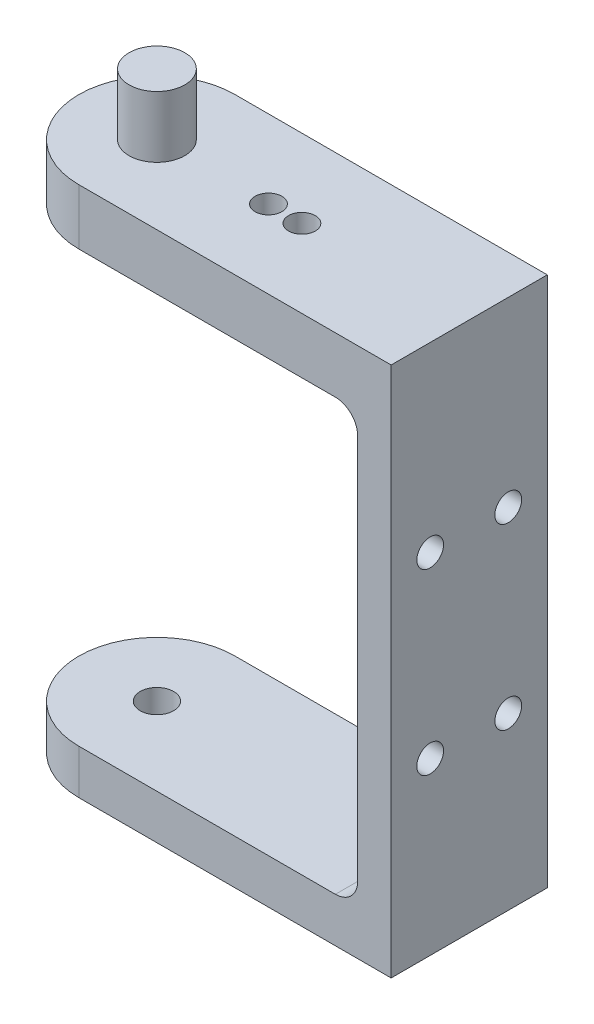
SolidWorks part; units mm, degrees
material "ABS"
ref_plane "Front Plane" through (0, 0, 0) normal (0, 0, 1) x (1, 0, 0)
ref_plane "Top Plane" through (0, 0, 0) normal (0, 1, 0) x (1, 0, 0)
ref_plane "Right Plane" through (0, 0, 0) normal (1, 0, 0) x (0, 0, -1)
ref_plane "Y+19_30" through (0, 19.3, 0) normal (0, 1, 0) x (1, 0, 0)
sketch "Sketch1" plane through (0, 19.3, 0) normal (0, 1, 0) x (1, 0, 0)
  line L0 (5.5, -7) -> (33.5, -7)
  line L1 (33.5, -7) -> (33.5, 7)
  line L2 (33.5, 7) -> (5.5, 7)
  arc A0 (5.5, 7) -> (5.5, -7) centre (5.5, 0) ccw
extrude "Boss-Extrude1" add sketch "Sketch1" along normal blind 5
ref_plane "Y-23_30" through (0, -23.3, 0) normal (0, 1, 0) x (1, 0, 0)
sketch "Sketch2" plane through (0, -23.3, 0) normal (0, 1, 0) x (1, 0, 0)
  line L0 (5.5, -7) -> (33.5, -7)
  line L1 (33.5, -7) -> (33.5, 7)
  line L2 (33.5, 7) -> (5.5, 7)
  arc A0 (5.5, 7) -> (5.5, -7) centre (5.5, 0) ccw
extrude "Boss-Extrude2" add sketch "Sketch2" along normal blind 4
sketch "Sketch3" plane through (0, 0, 0) normal (0, 0, 1) x (1, 0, 0)
  line L0 (7.7, -23.3) -> (-7.7, -23.3) construction
  line L1 (30.5, -23.3) -> (33.5, -23.3)
  line L2 (30.5, -23.3) -> (30.5, 24.3)
  line L3 (30.5, 24.3) -> (33.5, 24.3)
  line L4 (33.5, -23.3) -> (33.5, 24.3)
extrude "Boss-Extrude3" add sketch "Sketch3" along normal mid plane 14
ref_plane "Y+24_30" through (0, 24.3, 0) normal (0, 1, 0) x (1, 0, 0)
sketch "Sketch4" plane through (0, 24.3, 0) normal (0, 1, 0) x (1, 0, 0)
  circle A0 centre (5.5, 0) radius 2.5
extrude "Boss-Extrude4" add sketch "Sketch4" along normal blind 5.5
sketch "Sketch5" plane through (0, 19.3, 0) normal (0, 1, 0) x (1, 0, 0)
  circle A0 centre (5.5, 0) radius 3.7
extrude "Cut-Extrude2" cut sketch "Sketch5" along normal blind 1.6
sketch "Sketch6" plane through (0, 19.3, 0) normal (0, 1, 0) x (1, 0, 0)
  line L0 (5.5, -2.7) -> (20.7, -2.7)
  line L1 (20.7, -2.7) -> (20.7, 2.7)
  line L2 (20.7, 2.7) -> (5.5, 2.7)
  arc A0 (5.5, 2.7) -> (5.5, -2.7) centre (5.5, 0) ccw
extrude "Cut-Extrude4" cut sketch "Sketch6" along normal blind 1.6
ref_plane "Y+20_90" through (0, 20.9, 0) normal (0, 1, 0) x (1, 0, 0)
sketch "Sketch7" plane through (0, 20.9, 0) normal (0, 1, 0) x (1, 0, 0)
  circle A0 centre (5.5, 0) radius 2.5
extrude "Cut-Extrude6" cut sketch "Sketch7" along normal blind 1.6
sketch "Sketch8" plane through (0, -23.3, 0) normal (0, 1, 0) x (1, 0, 0)
  circle A0 centre (5.5, 0) radius 1.5
extrude "Cut-Extrude8" cut sketch "Sketch8" along normal blind 4
hole_wizard "M2 Clearance Hole1" positions "Sketch10" profile "Sketch9" hole size "M2" standard "ISO"
sketch "Sketch10" plane through (0, 24.3, 0) normal (0, 1, 0) x (1, 0, 0)
  point P0 (15.5, 0)
sketch "Sketch9" plane through (15.5, 24.3, 0) normal (1, 0, 0) x (0, 0, 1)
  line L0 (0, 0) -> (0, 5.721)
  line L1 (0, 5.721) -> (1.2, 5)
  line L2 (1.2, 5) -> (1.2, 0)
  line L5 (1.2, 0) -> (0, 0)
  line L10 (0, 5.721) -> (-1.2, 5) construction
  line L11 (0, -6.35) -> (0, 107.95) construction
  dimension "Hole Dia." = 2.4
  dimension "Hole Depth" = 5
  dimension "Drill Angle" = 118
hole_wizard "M2 Clearance Hole2" positions "Sketch12" profile "Sketch11" hole size "M2" standard "ISO"
sketch "Sketch12" plane through (0, 24.3, 0) normal (0, 1, 0) x (1, 0, 0)
  point P0 (18.5, 0)
sketch "Sketch11" plane through (18.5, 24.3, 0) normal (1, 0, 0) x (0, 0, 1)
  line L0 (0, 0) -> (0, 5.721)
  line L1 (0, 5.721) -> (1.2, 5)
  line L2 (1.2, 5) -> (1.2, 0)
  line L5 (1.2, 0) -> (0, 0)
  line L10 (0, 5.721) -> (-1.2, 5) construction
  line L11 (0, -6.35) -> (0, 107.95) construction
  dimension "Hole Dia." = 2.4
  dimension "Hole Depth" = 5
  dimension "Drill Angle" = 118
hole_wizard "M2 Clearance Hole3" positions "Sketch14" profile "Sketch13" hole size "M2" standard "ISO"
sketch "Sketch14" plane through (33.5, 0, 0) normal (1, 0, 0) x (0, 0, -1)
  point P0 (3.5, -8)
sketch "Sketch13" plane through (33.5, -8, -3.5) normal (0, 1, 0) x (0, 0, -1)
  line L0 (0, 0) -> (0, 35)
  line L1 (0, 35) -> (1.2, 35)
  line L2 (1.2, 35) -> (1.2, 0)
  line L5 (1.2, 0) -> (0, 0)
  line L11 (0, -6.35) -> (0, 107.95) construction
  dimension "Thru Hole Dia." = 2.4
  dimension "Thru Hole Depth" = 35
hole_wizard "M2 Clearance Hole4" positions "Sketch16" profile "Sketch15" hole size "M2" standard "ISO"
sketch "Sketch16" plane through (33.5, 0, 0) normal (1, 0, 0) x (0, 0, -1)
  point P0 (-3.5, -8)
sketch "Sketch15" plane through (33.5, -8, 3.5) normal (0, 1, 0) x (0, 0, -1)
  line L0 (0, 0) -> (0, 35)
  line L1 (0, 35) -> (1.2, 35)
  line L2 (1.2, 35) -> (1.2, 0)
  line L5 (1.2, 0) -> (0, 0)
  line L11 (0, -6.35) -> (0, 107.95) construction
  dimension "Thru Hole Dia." = 2.4
  dimension "Thru Hole Depth" = 35
hole_wizard "M2 Clearance Hole5" positions "Sketch18" profile "Sketch17" hole size "M2" standard "ISO"
sketch "Sketch18" plane through (33.5, 0, 0) normal (1, 0, 0) x (0, 0, -1)
  point P0 (3.5, 8)
sketch "Sketch17" plane through (33.5, 8, -3.5) normal (0, 1, 0) x (0, 0, -1)
  line L0 (0, 0) -> (0, 35)
  line L1 (0, 35) -> (1.2, 35)
  line L2 (1.2, 35) -> (1.2, 0)
  line L5 (1.2, 0) -> (0, 0)
  line L11 (0, -6.35) -> (0, 107.95) construction
  dimension "Thru Hole Dia." = 2.4
  dimension "Thru Hole Depth" = 35
hole_wizard "M2 Clearance Hole6" positions "Sketch20" profile "Sketch19" hole size "M2" standard "ISO"
sketch "Sketch20" plane through (33.5, 0, 0) normal (1, 0, 0) x (0, 0, -1)
  point P0 (-3.5, 8)
sketch "Sketch19" plane through (33.5, 8, 3.5) normal (0, 1, 0) x (0, 0, -1)
  line L0 (0, 0) -> (0, 35)
  line L1 (0, 35) -> (1.2, 35)
  line L2 (1.2, 35) -> (1.2, 0)
  line L5 (1.2, 0) -> (0, 0)
  line L11 (0, -6.35) -> (0, 107.95) construction
  dimension "Thru Hole Dia." = 2.4
  dimension "Thru Hole Depth" = 35
fillet "Fillet1" radius 2 2 edges at (30.5, -19.3, 0) (30.5, 19.3, 0)
